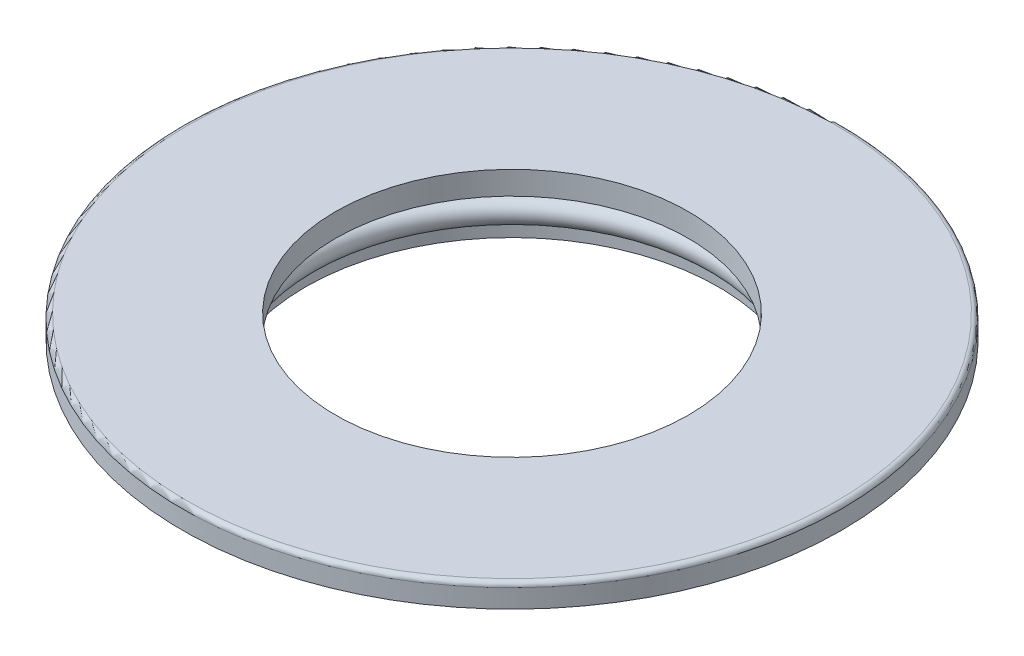
SolidWorks part; units mm, degrees
ref_plane "Front Plane" through (0, 0, 0) normal (0, 0, 1) x (1, 0, 0)
ref_plane "Top Plane" through (0, 0, 0) normal (0, 1, 0) x (1, 0, 0)
ref_plane "Right Plane" through (0, 0, 0) normal (1, 0, 0) x (0, 0, -1)
sketch "Sketch1" plane through (0, 0, 0) normal (0, 0, 1) x (1, 0, 0)
  line L2 (26.4283, 12.3301) -> (26.4283, 16.3301)
  line L3 (27.4283, 17.3301) -> (59.4283, 17.3301)
  line L4 (59.4283, 17.3301) -> (59.4283, 12.3301)
  line L5 (59.4283, 12.3301) -> (55.4283, 12.3301)
  line L15 (97.4283, 39.8926) -> (97.4283, -18.0087) construction
  line L17 (-33.6481, 0) -> (125.5026, 0) construction
  line L18 (47.9283, 7.3301) -> (47.9283, 0)
  line L19 (47.9283, 0) -> (52.9283, 0)
  line L20 (52.9283, 3) -> (52.9283, 0)
  line L21 (52.9283, 9.8301) -> (52.9283, 8)
  line L22 (42.9283, 12.3301) -> (26.4283, 12.3301)
  arc A6 (27.4283, 17.3301) -> (26.4283, 16.3301) centre (27.4283, 16.3301) ccw
  arc A12 (47.9283, 7.3301) -> (42.9283, 12.3301) centre (42.9283, 7.3301) ccw
  arc A13 (52.9283, 8) -> (52.9283, 3) centre (52.9283, 5.5) cw
  arc A14 (52.9283, 9.8301) -> (55.4283, 12.3301) centre (55.4283, 9.8301) cw
  point P19 (26.4283, 17.3301)
  point P22 (26.4283, 12.3301)
  dimension "D3" = 1.8301
  dimension "D4" = 2.5
  dimension "D9" = 5
  dimension "D10" = 33
  dimension "D11" = 21.5
  dimension "D12" = 1
  dimension "D13" = 4
  dimension "D2" = 38
  dimension "D8" = 97.4283
  dimension "D14" = 2.5
  dimension "D5" = 3
  dimension "D6" = 5
  dimension "D7" = 4
  dimension "D16" = 12.3301
  dimension "D17" = 7.3301
  dimension "D18" = 5
  dimension "D19" = 5
  dimension "D20" = 5.5
  dimension "D21" = 2.5
revolve "Revolve1" add sketch "Sketch1" angle 360 about L15
